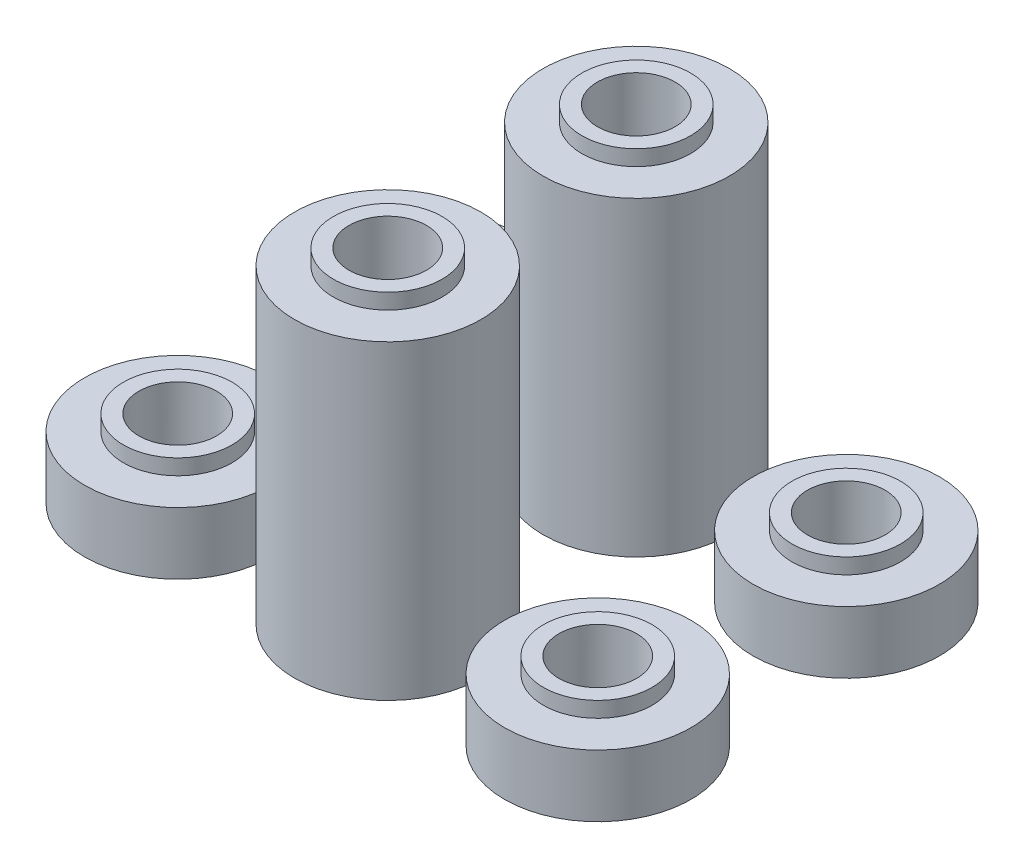
SolidWorks part; units mm, degrees
ref_plane "Alzado" through (0, 0, 0) normal (0, 0, 1) x (1, 0, 0)
ref_plane "Planta" through (0, 0, 0) normal (0, 1, 0) x (1, 0, 0)
ref_plane "Vista lateral" through (0, 0, 0) normal (1, 0, 0) x (0, 0, -1)
sketch "Croquis1" plane through (0, 0, 0) normal (0, 1, 0) x (1, 0, 0)
  circle A0 centre (0, 0) radius 6
  dimension "D1" = 12
extrude "Saliente-Extruir1" add sketch "Croquis1" along normal blind 20
sketch "Croquis2" plane through (0, 20, 0) normal (0, 1, 0) x (1, 0, 0)
  circle A0 centre (0, 0) radius 2.5
  dimension "D1" = 5
extrude "Cortar-Extruir1" cut sketch "Croquis2" against normal blind 20
sketch "Croquis3" plane through (0, 20, 0) normal (0, 1, 0) x (1, 0, 0)
  line L0 (0, 0) -> (-2.2409, -1.1083) construction
  line L1 (-2.2409, -1.1083) -> (-3.1373, -1.5516) construction
  circle A0 centre (0, 0) radius 2.5
  circle A1 centre (0, 0) radius 3.5
  circle A2 centre (0, 0) radius 2.5 construction
  dimension "D1" = 1
extrude "Saliente-Extruir2" add sketch "Croquis3" along normal blind 1
sketch "Croquis4" plane through (0, 0, 0) normal (0, -1, 0) x (1, 0, 0)
  circle A0 centre (0, 0) radius 4.5
  dimension "D1" = 9
extrude "Cortar-Extruir2" cut sketch "Croquis4" against normal blind 5
sketch "Croquis5" plane through (0, 0, 0) normal (0, 1, 0) x (1, 0, 0)
  line L0 (0, 0) -> (-13.522, 0) construction
  circle A0 centre (-13.522, 0) radius 6
  point P4 (-13.522, 0)
  dimension "D1" = 12
extrude "Saliente-Extruir3" add sketch "Croquis5" along normal blind 4 separate body
sketch "Croquis6" plane through (0, 4, 0) normal (0, 1, 0) x (1, 0, 0)
  circle A0 centre (-13.522, 0) radius 2.5
  dimension "D1" = 5
extrude "Cortar-Extruir3" cut sketch "Croquis6" against normal blind 4
sketch "Croquis7" plane through (0, 4, 0) normal (0, 1, 0) x (1, 0, 0)
  line L0 (-13.522, 0) -> (-15.9753, -0.4809) construction
  line L1 (-15.9753, -0.4809) -> (-16.9566, -0.6733) construction
  circle A0 centre (-13.522, 0) radius 2.5
  circle A1 centre (-13.522, 0) radius 3.5
  circle A4 centre (-13.522, 0) radius 2.5 construction
  dimension "D1" = 1
extrude "Saliente-Extruir4" add sketch "Croquis7" along normal blind 1
sketch "Croquis8" plane through (0, 0, 0) normal (0, -1, 0) x (1, 0, 0)
  circle A1 centre (-13.522, 0) radius 3.5
  circle A2 centre (-13.522, 0) radius 3.5
  circle A3 centre (-13.522, 0) radius 2.5
  circle A4 centre (-13.522, 0) radius 2.5
  dimension "D1" = 0
  dimension "D2" = 0
extrude "Cortar-Extruir4" cut sketch "Croquis8" against normal blind 1
mirror "Simetría2" about plane through (0, 0, 0) normal (1, 0, 0) of bodies 108
ref_plane "Plano1" through (0, 0, 8) normal (0, 0, 1) x (1, 0, 0)
mirror "Simetría3" about plane through (0, 0, 8) normal (0, 0, 1) of bodies 109 104 108
